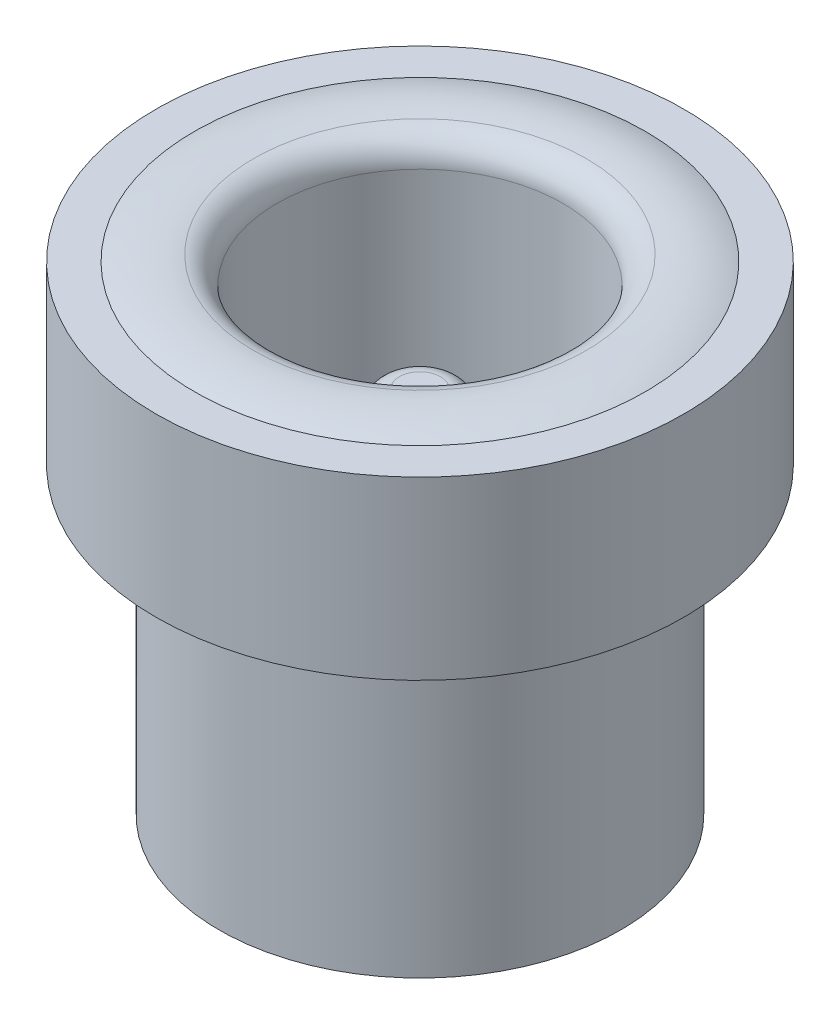
SolidWorks part; units mm, degrees
material "PE High Density"
ref_plane "Front Plane" through (0, 0, 0) normal (0, 0, 1) x (1, 0, 0)
ref_plane "Top Plane" through (0, 0, 0) normal (0, 1, 0) x (1, 0, 0)
ref_plane "Right Plane" through (0, 0, 0) normal (1, 0, 0) x (0, 0, -1)
sketch "Sketch1" plane through (0, 0, 0) normal (0, 1, 0) x (1, 0, 0)
  circle A0 centre (0, 0) radius 4.8
  dimension "D1" = 9.6
extrude "Boss-Extrude1" add sketch "Sketch1" along normal blind 3.2
sketch "Sketch2" plane through (0, 0, 0) normal (0, -1, 0) x (1, 0, 0)
  circle A0 centre (0, 0) radius 3.65
  dimension "D1" = 7.3
extrude "Boss-Extrude2" add sketch "Sketch2" along normal blind 5.5
sketch "Sketch3" plane through (0, 3.2, 0) normal (0, 1, 0) x (1, 0, 0)
  circle A0 centre (0, 0) radius 2.6
extrude "Cut-Extrude1" cut sketch "Sketch3" against normal blind 8
sketch "Sketch4" plane through (0, 0, 0) normal (0, 0, 1) x (1, 0, 0)
  line L0 (2.6, 3.2) -> (-2.6, 3.2) construction
  line L1 (2.6, 3.2) -> (-2.6, 3.2) construction
  line L2 (4.8, 3.2) -> (-4.8, 3.2) construction
  line L3 (-4.1, 3.2) -> (-2.6, 3.2)
  line L4 (0, 0) -> (0, 5.264) construction
  arc A0 (-2.6, 3.2) -> (-4.1, 3.2) centre (-3.35, 1.2) ccw
  dimension "D1" = 0.7
  dimension "D2" = 2
revolve "Revolve1" add sketch "Sketch4" angle 360 about L4
fillet "Fillet1" radius 0.5 1 edges at (0, 3.2, -2.6)
sketch "Sketch5" plane through (0, -4.8, 0) normal (0, 1, 0) x (1, 0, 0)
  circle A0 centre (0, 0) radius 0.75
extrude "Boss-Extrude3" add sketch "Sketch5" along normal blind 6
fillet "Fillet2" radius 0.375 1 edges at (0, 1.2, 0.75)
